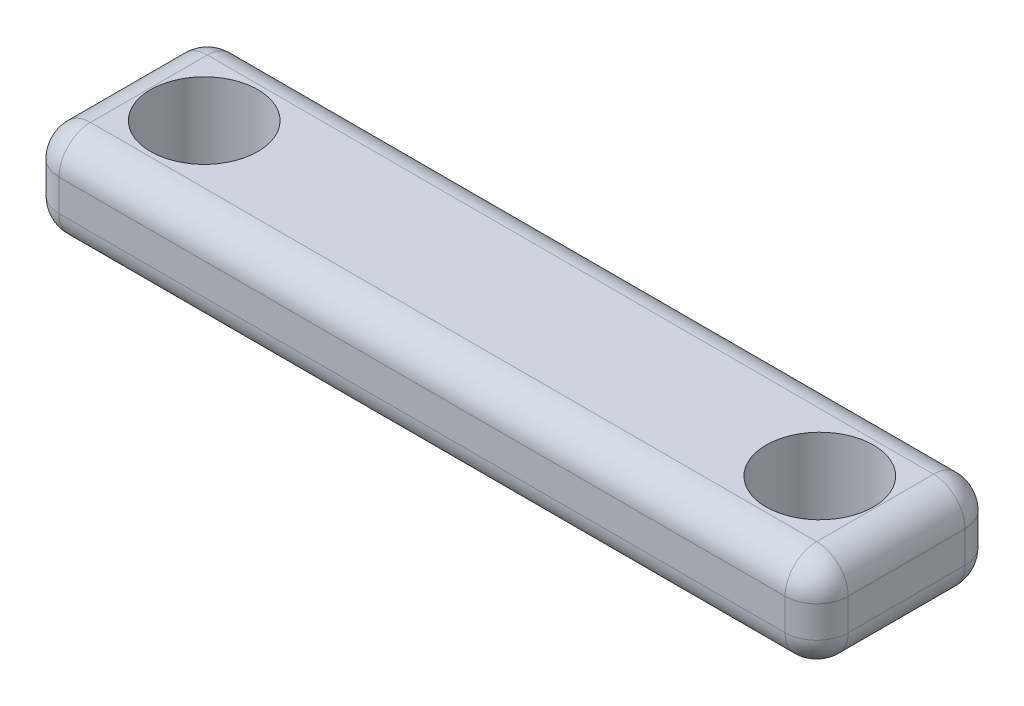
SolidWorks part; units mm, degrees
ref_plane "Front Plane" through (0, 0, 0) normal (0, 0, 1) x (1, 0, 0)
ref_plane "Top Plane" through (0, 0, 0) normal (0, 1, 0) x (1, 0, 0)
ref_plane "Right Plane" through (0, 0, 0) normal (1, 0, 0) x (0, 0, -1)
sketch "Sketch1" plane through (0, 0, 0) normal (0, 1, 0) x (1, 0, 0)
  line L0 (0, 2.85) -> (2.75, 2.85) construction
  line L1 (0, 0) -> (25, 0)
  line L2 (0, 0) -> (0, 5.7)
  line L3 (0, 5.7) -> (25, 5.7)
  line L4 (25, 0) -> (25, 5.7)
  line L5 (2.75, 2.85) -> (22.25, 2.85) construction
  line L6 (22.25, 2.85) -> (25, 2.85) construction
  circle A0 centre (2.75, 2.85) radius 1.7
  circle A1 centre (22.25, 2.85) radius 1.7
  dimension "D3" = 3.4
  dimension "D1" = 25
  dimension "D2" = 5.7
  dimension "D4" = 19.5
extrude "Boss-Extrude1" add sketch "Sketch1" along normal blind 3
fillet "Fillet1" radius 1 12 edges at (25, 3, -2.85) (25, 0, -2.85) (0, 3, -2.85) (0, 0, -2.85) (25, 1.5, -5.7) (12.5, 3, -5.7) (0, 1.5, -5.7) (12.5, 0, -5.7) (0, 1.5, 0) (12.5, 3, 0) (25, 1.5, 0) (12.5, 0, 0)
